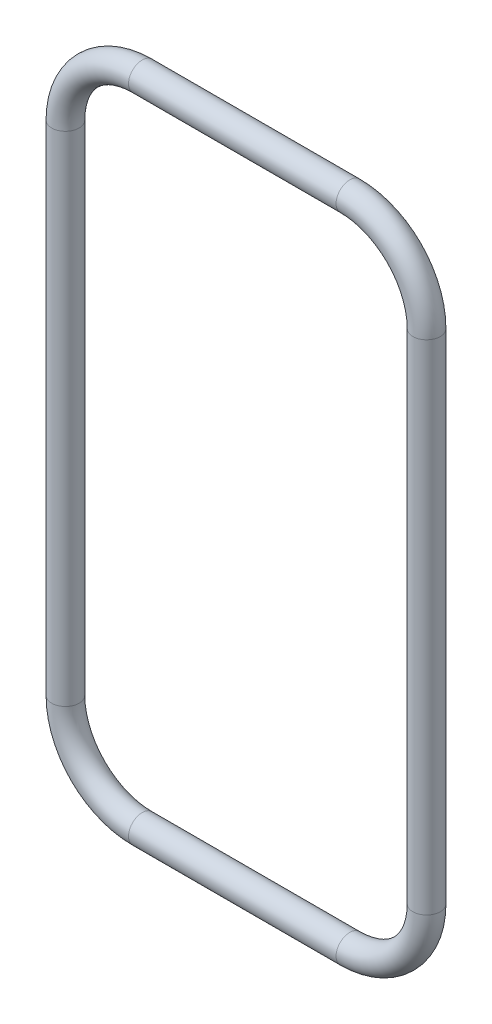
SolidWorks part; units mm, degrees
ref_plane "Front Plane" through (0, 0, 0) normal (0, 0, 1) x (1, 0, 0)
ref_plane "Top Plane" through (0, 0, 0) normal (0, 1, 0) x (1, 0, 0)
ref_plane "Right Plane" through (0, 0, 0) normal (1, 0, 0) x (0, 0, -1)
sketch "Sketch1" plane through (0, 0, 0) normal (0, 0, 1) x (1, 0, 0)
  line L12 (69.2499, 20) -> (69.2499, 79.9998)
  line L13 (34.9999, 10.75) -> (59.9999, 10.75)
  line L14 (25.75, 79.9998) -> (25.75, 20)
  line L15 (59.9999, 89.2498) -> (34.9999, 89.2498)
  arc A12 (59.9999, 10.75) -> (69.2499, 20) centre (59.9999, 20) ccw
  arc A13 (25.75, 20) -> (34.9999, 10.75) centre (34.9999, 20) ccw
  arc A14 (34.9999, 89.2498) -> (25.75, 79.9998) centre (34.9999, 79.9998) ccw
  arc A15 (69.2499, 79.9998) -> (59.9999, 89.2498) centre (59.9999, 79.9998) ccw
sweep "Sweep1" add path "Sketch1" circular profile diameter 3.3 parameters "D3"=3.3
